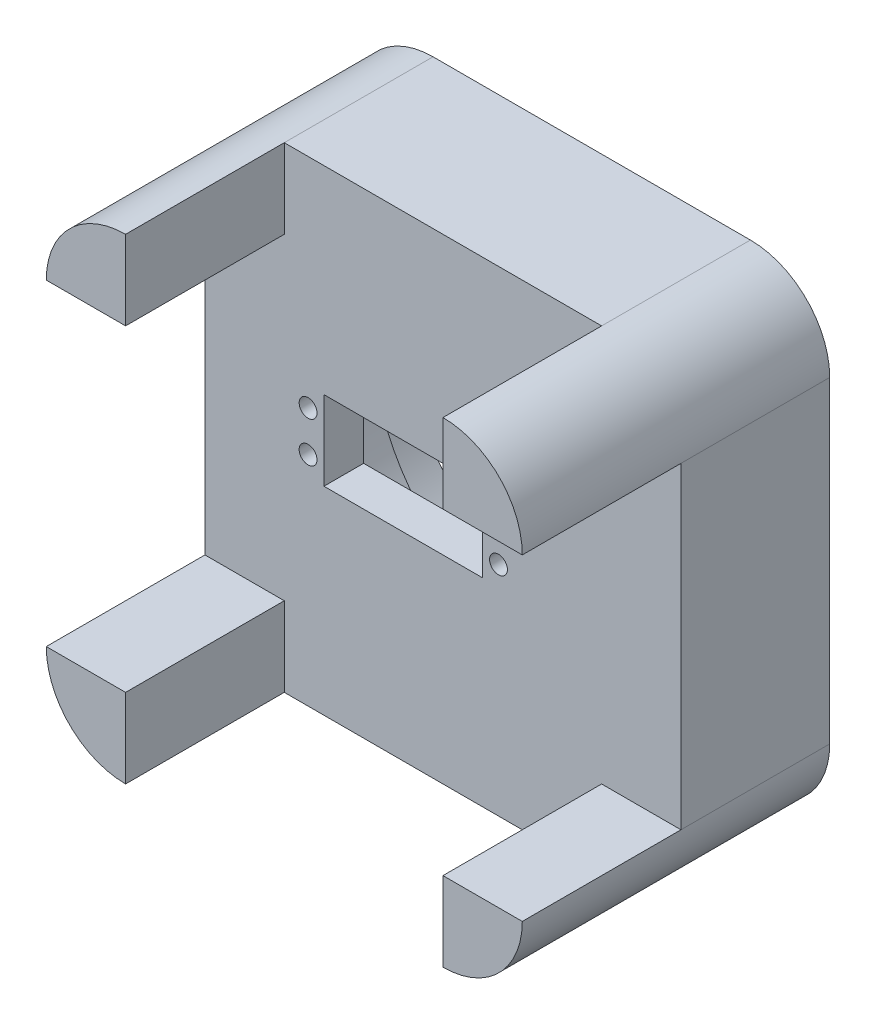
SolidWorks part; units mm, degrees
ref_plane "前视基准面" through (0, 0, 0) normal (0, 0, 1) x (1, 0, 0)
ref_plane "上视基准面" through (0, 0, 0) normal (0, 1, 0) x (1, 0, 0)
ref_plane "右视基准面" through (0, 0, 0) normal (1, 0, 0) x (0, 0, -1)
sketch "草图1" plane through (0, 0, 0) normal (0, 0, 1) x (1, 0, 0)
  line L1 (-60, 60) -> (60, 60)
  line L2 (-60, 60) -> (-60, -60)
  line L3 (-60, -60) -> (60, -60)
  line L4 (60, 60) -> (60, -60)
  line L5 (-60, 60) -> (60, -60) construction
  line L6 (-60, -60) -> (60, 60) construction
  point P0 (0, 0)
extrude "凸台-拉伸1" add sketch "草图1" along normal blind 100
sketch "草图2" plane through (0, 0, 0) normal (0, 0, -1) x (-1, 0, 0)
  circle A0 centre (0, 0) radius 47.5
extrude "切除-拉伸1" cut sketch "草图2" against normal blind 10
sketch "草图3" plane through (0, 0, 10) normal (0, 0, -1) x (-1, 0, 0)
  circle A0 centre (0, 0) radius 45
extrude "切除-拉伸2" cut sketch "草图3" against normal blind 17.5
sketch "草图4" plane through (0, 0, 100) normal (0, 0, 1) x (1, 0, 0)
  line L0 (-60, 60) -> (60, 60)
  line L1 (60, 60) -> (60, -60)
  line L2 (60, -60) -> (-60, -60)
  line L3 (-60, -60) -> (-60, 60)
extrude "切除-拉伸3" cut sketch "草图4" against normal blind 49.5
sketch "草图6" plane through (0, 0, 50.5) normal (0, 0, 1) x (1, 0, 0)
  line L1 (-60, 60) -> (60, 60)
  line L2 (-60, 60) -> (-60, -60)
  line L3 (-60, -60) -> (60, -60)
  line L4 (60, 60) -> (60, -60)
  line L5 (-60, 60) -> (60, -60) construction
  line L6 (-60, -60) -> (60, 60) construction
  point P0 (0, 0)
extrude "切除-拉伸5" cut sketch "草图6" against normal blind 13
sketch "草图7" plane through (0, 0, 27.5) normal (0, 0, -1) x (-1, 0, 0)
  line L0 (-10, 10) -> (30, 10)
  line L1 (-10, 0) -> (-10, 10)
  line L2 (-10, 0) -> (-10, -10)
  line L3 (30, 10) -> (30, -10)
  line L4 (30, -10) -> (-10, -10)
extrude "切除-拉伸6" cut sketch "草图7" against normal blind 13
sketch "草图8" plane through (0, 0, 27.5) normal (0, 0, -1) x (-1, 0, 0)
  line L0 (10, 10) -> (10, -10)
  line L1 (30, 10) -> (-10, 10) construction
  line L2 (-10, -10) -> (30, -10) construction
  circle A0 centre (-14, -5.1) radius 2.25
  circle A1 centre (-14, 5.1) radius 2.25
  circle A2 centre (34, -5.1) radius 2.25
  circle A3 centre (34, 5.1) radius 2.25
  point P16 (0, 0)
extrude "切除-拉伸7" cut sketch "草图8" against normal blind 13 contours A1 | A0
sketch "草图10" plane through (0, 0, 27.5) normal (0, 0, -1) x (-1, 0, 0)
  circle A0 centre (34, 5.1) radius 2.25
  circle A1 centre (34, -5.1) radius 2.25
extrude "切除-拉伸8" cut sketch "草图10" against normal blind 13
fillet "圆角1" radius 20 1 edges at (60, 60, 18.75)
fillet "圆角2" radius 20 3 edges at (60, -60, 18.75) (-60, -60, 18.75) (-60, 60, 18.75)
sketch "草图11" plane through (0, 0, 0) normal (0, 0, -1) x (-1, 0, 0)
  circle A2 centre (-38.8909, 38.8909) radius 1.5
  circle A3 centre (38.8909, 38.8909) radius 1.5
  circle A4 centre (38.8909, -38.8909) radius 1.5
  circle A5 centre (-38.8909, -38.8909) radius 1.5
  point P16 (0, 0)
  dimension "D1" = 4
extrude "切除-拉伸9" cut sketch "草图11" against normal blind 10
sketch "草图12" plane through (0, 0, 37.5) normal (0, 0, 1) x (1, 0, 0)
  line L0 (-40, 40) -> (-40, 60)
  line L1 (-40, 40) -> (-60, 40)
  line L2 (40, 40) -> (40, 60)
  line L3 (40, 40) -> (60, 40)
  line L4 (40, -40) -> (60, -40)
  line L5 (40, -40) -> (40, -60)
  line L6 (-40, -40) -> (-40, -60)
  line L7 (-40, -40) -> (-60, -40)
  arc A0 (-40, 60) -> (-60, 40) centre (-40, 40) ccw
  arc A1 (60, 40) -> (40, 60) centre (40, 40) ccw
  arc A2 (40, -60) -> (60, -40) centre (40, -40) ccw
  arc A3 (-60, -40) -> (-40, -60) centre (-40, -40) ccw
  point P18 (0, 0)
  dimension "D1" = 4
extrude "凸台-拉伸3" add sketch "草图12" along normal blind 40
